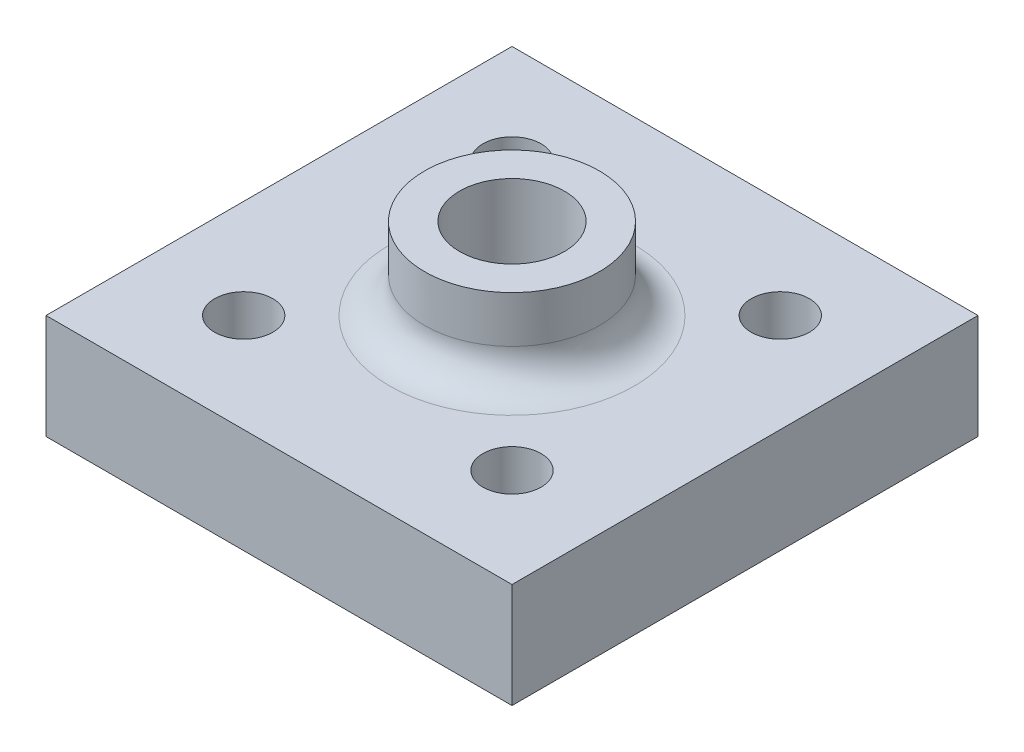
SolidWorks part; units mm, degrees
ref_plane "Front Plane" through (0, 0, 0) normal (0, 0, 1) x (1, 0, 0)
ref_plane "Top Plane" through (0, 0, 0) normal (0, 1, 0) x (1, 0, 0)
ref_plane "Right Plane" through (0, 0, 0) normal (1, 0, 0) x (0, 0, -1)
sketch "Sketch1" plane through (0, 0, 0) normal (0, 1, 0) x (1, 0, 0)
  line L1 (-20, 20) -> (20, 20)
  line L2 (-20, 20) -> (-20, -20)
  line L3 (-20, -20) -> (20, -20)
  line L4 (20, 20) -> (20, -20)
  line L5 (-20, 20) -> (20, -20) construction
  line L6 (-20, -20) -> (20, 20) construction
  line L7 (7.5056, 0) -> (3.7528, 6.5)
  line L8 (3.7528, 6.5) -> (-3.7528, 6.5)
  line L9 (-3.7528, 6.5) -> (-7.5056, 0)
  line L10 (-7.5056, 0) -> (-3.7528, -6.5)
  line L11 (-3.7528, -6.5) -> (3.7528, -6.5)
  line L12 (3.7528, -6.5) -> (7.5056, 0)
  circle A0 centre (0, 0) radius 6.5 construction
  point P0 (0, 0)
  dimension "D2" = 13
  dimension "D1" = 40
extrude "Boss-Extrude1" add sketch "Sketch1" along normal blind 6
sketch "Sketch2" plane through (0, 6, 0) normal (0, 1, 0) x (1, 0, 0)
  line L1 (-20, 20) -> (20, 20)
  line L2 (-20, 20) -> (-20, -20)
  line L3 (-20, -20) -> (20, -20)
  line L4 (20, 20) -> (20, -20)
  circle A0 centre (0, 0) radius 4.5
  dimension "D1" = 9
extrude "Boss-Extrude2" add sketch "Sketch2" along normal blind 3
sketch "Sketch3" plane through (0, 9, 0) normal (0, 1, 0) x (1, 0, 0)
  line L0 (-20, 20) -> (20, -20) construction
  line L1 (-20, -20) -> (20, 20) construction
  circle A0 centre (-11.5147, 11.5147) radius 2.5
  circle A1 centre (11.5147, 11.5147) radius 2.5
  circle A2 centre (11.5147, -11.5147) radius 2.5
  circle A3 centre (-11.5147, -11.5147) radius 2.5
  dimension "D1" = 5
  dimension "D2" = 12
  dimension "D3" = 12
  dimension "D4" = 12
  dimension "D5" = 12
extrude "Cut-Extrude1" cut sketch "Sketch3" against normal blind 24
sketch "Sketch4" plane through (0, 9, 0) normal (0, 1, 0) x (1, 0, 0)
  circle A0 centre (0, 0) radius 4.5
  circle A1 centre (0, 0) radius 7.5
  dimension "D1" = 3
extrude "Boss-Extrude3" add sketch "Sketch4" along normal blind 7
fillet "Fillet1" radius 3 1 edges at (0, 9, 7.5)
